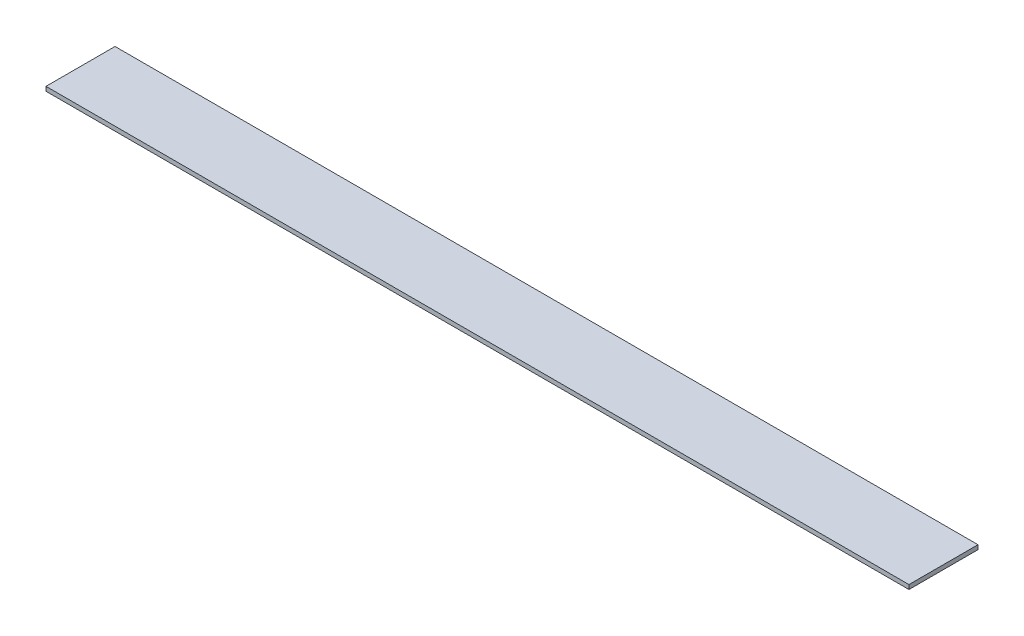
SolidWorks part; units mm, degrees
material "Nylon 101"
ref_plane "Front Plane" through (0, 0, 0) normal (0, 0, 1) x (1, 0, 0)
ref_plane "Top Plane" through (0, 0, 0) normal (0, 1, 0) x (1, 0, 0)
ref_plane "Right Plane" through (0, 0, 0) normal (1, 0, 0) x (0, 0, -1)
sketch "Sketch1" plane through (0, 0, 0) normal (0, 1, 0) x (1, 0, 0)
  line L1 (0, 0) -> (317.5, 0)
  line L2 (0, 0) -> (0, 25.4)
  line L3 (0, 25.4) -> (317.5, 25.4)
  line L4 (317.5, 0) -> (317.5, 25.4)
  dimension "D1" = 25.4
  dimension "D2" = 317.5
extrude "Boss-Extrude1" add sketch "Sketch1" along normal blind 1.5875
